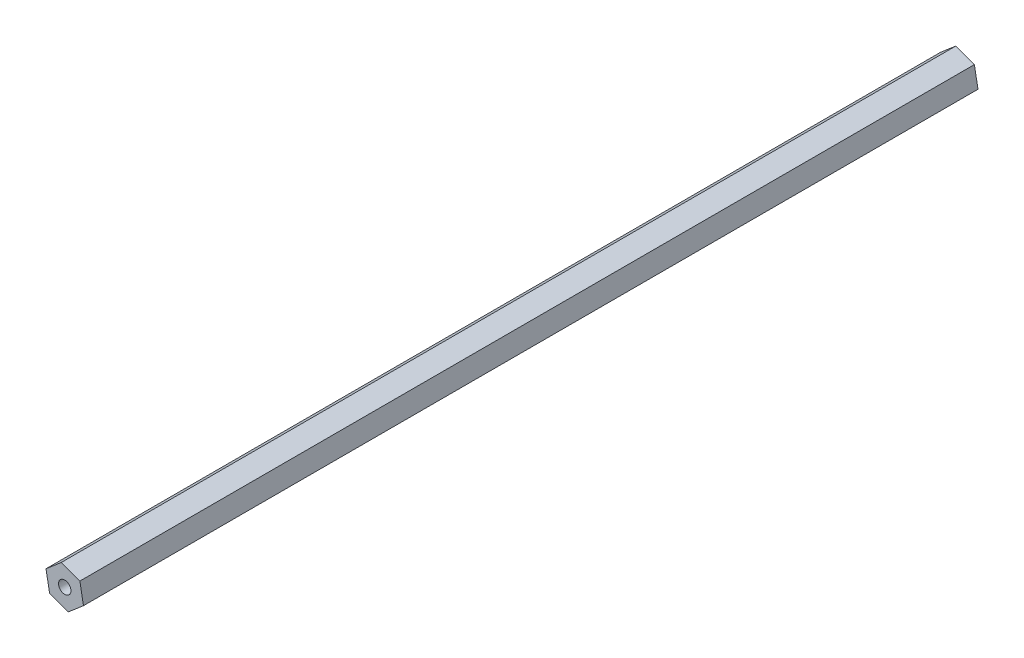
SolidWorks part; units mm, degrees
ref_plane "Front Plane" through (0, 0, 0) normal (0, 0, 1) x (1, 0, 0)
ref_plane "Top Plane" through (0, 0, 0) normal (0, 1, 0) x (1, 0, 0)
ref_plane "Right Plane" through (0, 0, 0) normal (1, 0, 0) x (0, 0, -1)
sketch "Sketch1" plane through (0, 0, 0) normal (0, 0, 1) x (1, 0, 0)
  line L1 (3.7707, -1.3349) -> (3.0414, 2.5981)
  line L2 (3.0414, 2.5981) -> (-0.7293, 3.933)
  line L3 (-0.7293, 3.933) -> (-3.7707, 1.3349)
  line L4 (-3.7707, 1.3349) -> (-3.0414, -2.5981)
  line L5 (-3.0414, -2.5981) -> (0.7293, -3.933)
  line L6 (0.7293, -3.933) -> (3.7707, -1.3349)
  circle A0 centre (0, 0) radius 4 construction
  circle A1 centre (0, 0) radius 3.4641 construction
  dimension "D1" = 8
  dimension "D2" = 2.5981
  dimension "D3" = 4
extrude "Boss-Extrude1" add sketch "Sketch1" along normal blind 180
sketch "Sketch4" plane through (0, 0, 0) normal (0, 0, -1) x (-1, 0, 0)
  circle A0 centre (0, 0) radius 1.25
  dimension "D1" = 2.5
extrude "Cut-Extrude1" cut sketch "Sketch4" against normal blind 5
ref_plane "Plane1" through (0, 0, 90) normal (0, 0, 1) x (1, 0, 0)
mirror "Mirror1" about plane through (0, 0, 90) normal (0, 0, 1) of "Cut-Extrude1"
